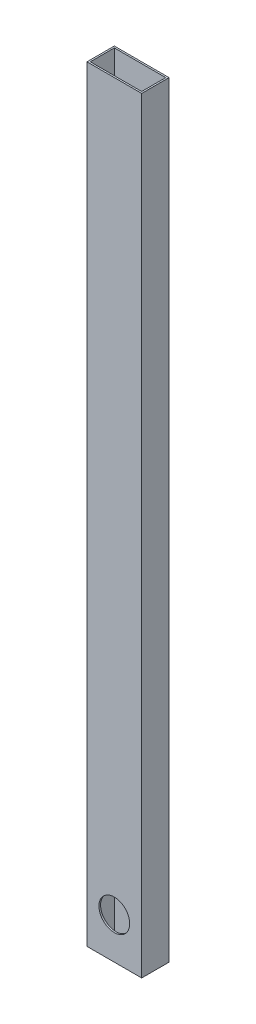
SolidWorks part; units mm, degrees
ref_plane "Front Plane" through (0, 0, 0) normal (0, 0, 1) x (1, 0, 0)
ref_plane "Top Plane" through (0, 0, 0) normal (0, 1, 0) x (1, 0, 0)
ref_plane "Right Plane" through (0, 0, 0) normal (1, 0, 0) x (0, 0, -1)
sketch "Sketch1" plane through (0, 0, 0) normal (0, 1, 0) x (1, 0, 0)
  line L1 (0, 0) -> (-50.8, 0)
  line L2 (0, 0) -> (0, -25.4)
  line L3 (0, -25.4) -> (-50.8, -25.4)
  line L4 (-50.8, 0) -> (-50.8, -25.4)
  dimension "D1" = 50.8
  dimension "D2" = 25.4
extrude "Extrude-Thin1" add sketch "Sketch1" along normal blind 711.2 thin thin type one direction reverse wall 1.524
sketch "Sketch2" plane through (0, 0, 25.4) normal (0, 0, 1) x (1, 0, 0)
  line L0 (-50.8, 0) -> (0, 0) construction
  circle A0 centre (-25.4, 38.1) radius 14.2875
  dimension "D1" = 28.575
  dimension "D2" = 38.1
extrude "Cut-Extrude1" cut sketch "Sketch2" against normal through all both and the other way through all
